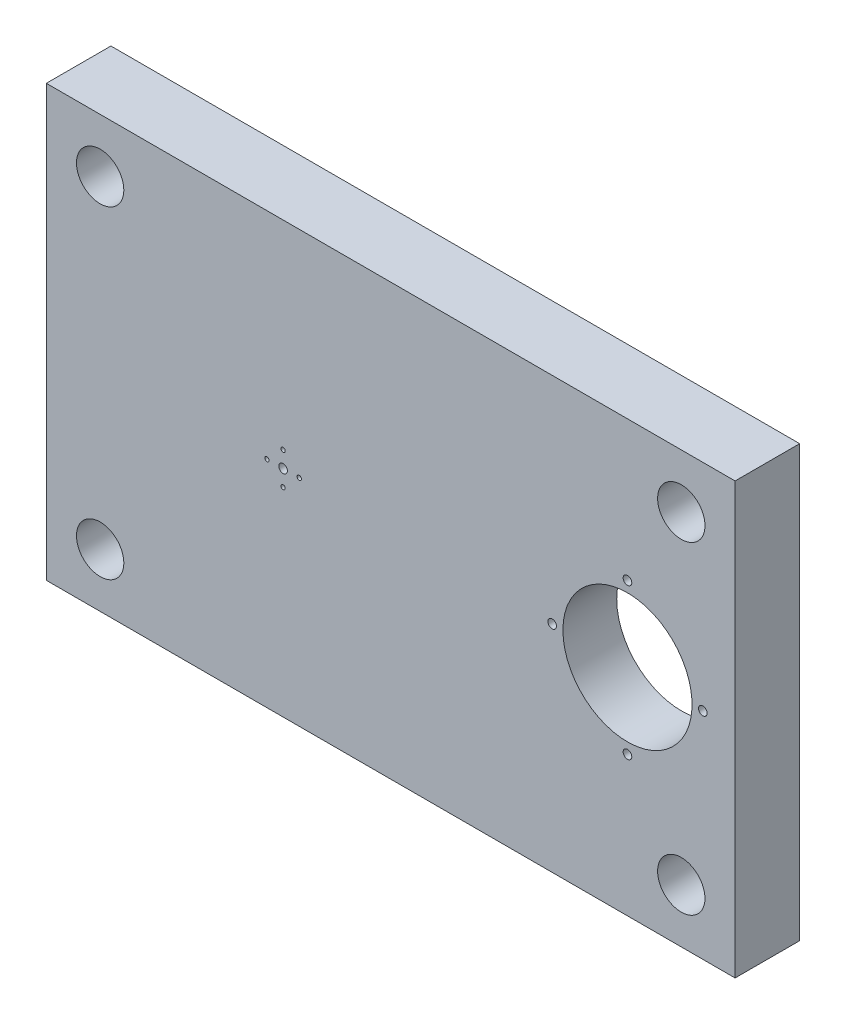
SolidWorks part; units mm, degrees
material "Nylon 6/10"
ref_plane "Front" through (0, 0, 0) normal (0, 0, 1) x (1, 0, 0)
ref_plane "Top" through (0, 0, 0) normal (0, 1, 0) x (1, 0, 0)
ref_plane "Right" through (0, 0, 0) normal (1, 0, 0) x (0, 0, -1)
sketch "Sketch1" plane through (0, 0, 0) normal (0, 0, 1) x (1, 0, 0)
  line L1 (0, 0) -> (320, 0)
  line L2 (0, 0) -> (0, 200)
  line L3 (0, 200) -> (320, 200)
  line L4 (320, 0) -> (320, 200)
  line L5 (25, 175) -> (295, 175) construction
  line L6 (25, 175) -> (25, 25) construction
  line L7 (25, 25) -> (295, 25) construction
  line L8 (295, 175) -> (295, 25) construction
  circle A0 centre (25, 175) radius 8.1
  circle A1 centre (295, 175) radius 8.1
  circle A2 centre (25, 25) radius 8.1
  circle A3 centre (295, 25) radius 8.1
  dimension "D3" = 16.2
  dimension "D1" = 320
  dimension "D2" = 200
  dimension "D4" = 25
  dimension "D5" = 25
  dimension "D6" = 25
  dimension "D7" = 25
extrude "Boss-Extrude1" add sketch "Sketch1" along normal blind 30
sketch "Sketch2" plane through (0, 0, 30) normal (0, 0, 1) x (1, 0, 0)
  circle A4 centre (295, 175) radius 11
  circle A5 centre (25, 175) radius 11
  circle A6 centre (25, 25) radius 11
  circle A7 centre (295, 25) radius 11
  dimension "D1" = 22
extrude "Cut-Extrude1" cut sketch "Sketch2" against normal blind 20
sketch "Sketch3" plane through (0, 0, 0) normal (0, 0, -1) x (-1, 0, 0)
  line L1 (0, 200) -> (0, 0) construction
  line L2 (-320, 200) -> (0, 200) construction
  circle A0 centre (-110, 100) radius 58.5
  circle A1 centre (-110, 100) radius 75 construction
  dimension "D1" = 117
  dimension "D2" = 150
  dimension "D3" = 110
  dimension "D4" = 100
extrude "Cut-Extrude2" cut sketch "Sketch3" against normal blind 5
sketch "Sketch4" plane through (0, 0, 5) normal (0, 0, -1) x (-1, 0, 0)
  line L1 (-110, 116) -> (11.3741, 116)
  line L3 (-110, 84) -> (11.3741, 84)
  line L4 (11.3741, 116) -> (11.3741, 84)
  arc A0 (-110, 116) -> (-110, 84) centre (-110, 100) ccw
  dimension "D1" = 32
extrude "Cut-Extrude3" cut sketch "Sketch4" against normal blind 20
sketch "Sketch5" plane through (0, 0, 25) normal (0, 0, -1) x (-1, 0, 0)
  circle A0 centre (-110, 100) radius 2
  dimension "D1" = 4
extrude "Cut-Extrude4" cut sketch "Sketch5" against normal through all
sketch "Sketch6" plane through (0, 0, 0) normal (0, 0, -1) x (-1, 0, 0)
  line L0 (-320, 100) -> (-270, 100) construction
  line L1 (-320, 0) -> (-320, 200) construction
  circle A0 centre (-270, 100) radius 40
  dimension "D1" = 80
  dimension "D2" = 50
extrude "Cut-Extrude5" cut sketch "Sketch6" against normal blind 5
sketch "Sketch7" plane through (0, 0, 0) normal (0, 0, -1) x (-1, 0, 0)
  circle A0 centre (-270, 100) radius 30
  dimension "D1" = 60
extrude "Cut-Extrude6" cut sketch "Sketch7" against normal through all
sketch "Sketch8" plane through (0, 0, 0) normal (0, 0, -1) x (-1, 0, 0)
  circle A0 centre (-270, 100) radius 35 construction
  circle A1 centre (-270, 135) radius 2
  circle A2 centre (-235, 100) radius 2
  circle A3 centre (-270, 65) radius 2
  circle A4 centre (-305, 100) radius 2
  dimension "D1" = 70
  dimension "D2" = 4
extrude "Cut-Extrude7" cut sketch "Sketch8" against normal through all
sketch "Sketch9" plane through (0, 0, 30) normal (0, 0, 1) x (1, 0, 0)
  circle A0 centre (110, 100) radius 7.5 construction
  circle A1 centre (110, 107.5) radius 1
  circle A2 centre (117.5, 100) radius 1
  circle A3 centre (110, 92.5) radius 1
  circle A4 centre (102.5, 100) radius 1
  dimension "D1" = 15
  dimension "D2" = 2
extrude "Cut-Extrude8" cut sketch "Sketch9" against normal through all
cosmetic thread "Cosmetic Thread1" parameters "D1"=2, "D2"=2.5
cosmetic thread "Cosmetic Thread2" parameters "D1"=2, "D2"=2.5
cosmetic thread "Cosmetic Thread3" parameters "D1"=5, "D2"=2.5
cosmetic thread "Cosmetic Thread4" parameters "D1"=5, "D2"=2.5
